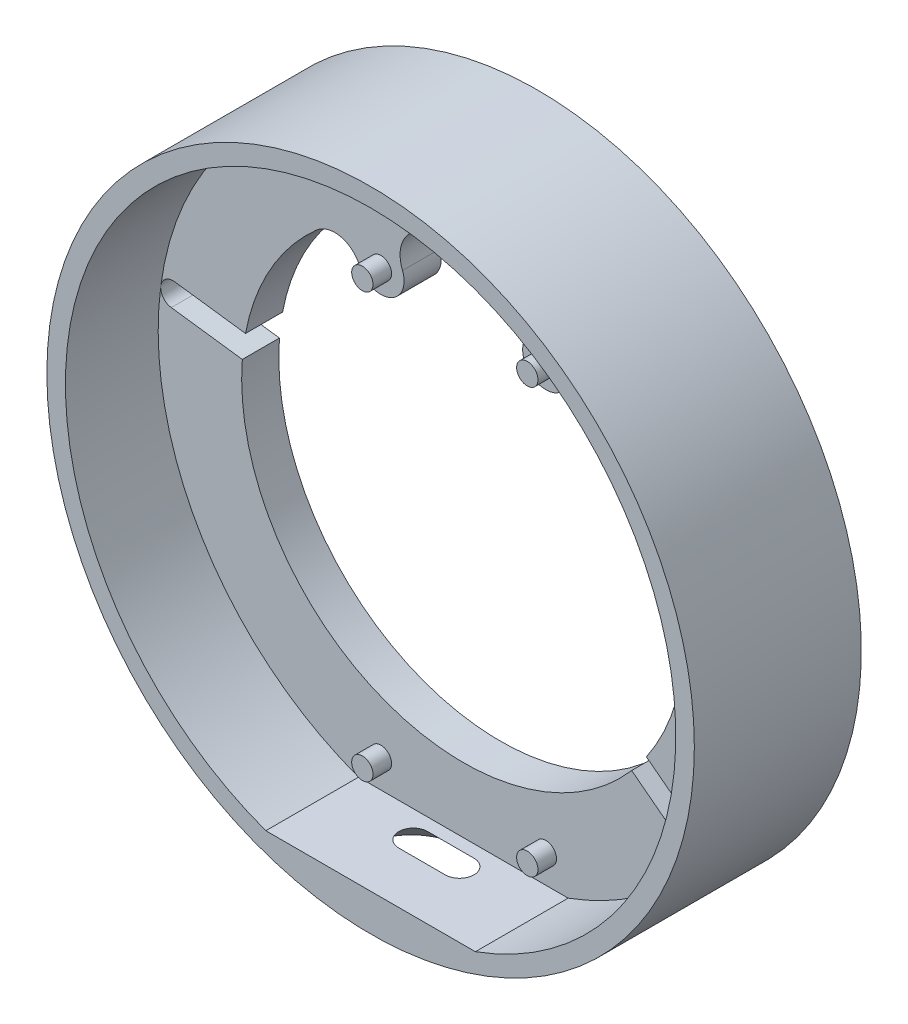
SolidWorks part; units mm, degrees
ref_plane "Plan de face" through (0, 0, 0) normal (0, 0, 1) x (1, 0, 0)
ref_plane "Plan de dessus" through (0, 0, 0) normal (0, 1, 0) x (1, 0, 0)
ref_plane "Plan de droite" through (0, 0, 0) normal (1, 0, 0) x (0, 0, -1)
sketch "Esquisse_carte_affichage" plane through (0, 0, 0) normal (0, 0, 1) x (1, 0, 0)
  circle A0 centre (19.25, 25.1) radius 0.5
  circle A1 centre (25.07, -19.23) radius 0.5
  circle A2 centre (29.18, 12.09) radius 0.5
  circle A3 centre (31.32, -4.14) radius 0.5
  circle A4 centre (-29.21, -12.07) radius 0.5
  circle A5 centre (-31.32, 4.14) radius 0.5
  circle A6 centre (-26.4935, -7.4094) radius 0.25
  circle A7 centre (-23.6728, -14.0139) radius 0.25
  circle A8 centre (-19.2392, -19.6637) radius 0.25
  circle A9 centre (-13.4943, -23.973) radius 0.25
  circle A10 centre (-6.8298, -26.6487) radius 0.25
  circle A11 centre (0.3, -27.5085) radius 0.25
  circle A12 centre (7.4094, -26.4935) radius 0.25
  circle A13 centre (14.0139, -23.6728) radius 0.25
  circle A14 centre (19.6637, -19.2392) radius 0.25
  circle A15 centre (23.973, -13.4943) radius 0.25
  circle A16 centre (26.6487, -6.8298) radius 0.25
  circle A17 centre (27.5085, 0.3) radius 0.25
  circle A18 centre (26.4935, 7.4094) radius 0.25
  circle A19 centre (23.6728, 14.0139) radius 0.25
  circle A20 centre (19.2392, 19.6637) radius 0.25
  circle A21 centre (13.4943, 23.973) radius 0.25
  circle A22 centre (6.8298, 26.6487) radius 0.25
  circle A23 centre (-0.3, 27.5085) radius 0.25
  circle A24 centre (-7.4094, 26.4935) radius 0.25
  circle A25 centre (-14.0139, 23.6728) radius 0.25
  circle A26 centre (-19.6637, 19.2392) radius 0.25
  circle A27 centre (-23.973, 13.4943) radius 0.25
  circle A28 centre (-26.6487, 6.8298) radius 0.25
  circle A29 centre (-27.5085, -0.3) radius 0.25
  circle A30 centre (-30.2, -7.1) radius 0.25
  circle A31 centre (-26.5986, -15.746) radius 0.25
  circle A32 centre (-28.1305, -7.8674) radius 0.25
  circle A33 centre (-21.6169, -22.0937) radius 0.25
  circle A34 centre (-25.1358, -14.8801) radius 0.25
  circle A35 centre (-15.162, -26.9359) radius 0.25
  circle A36 centre (-20.428, -20.8785) radius 0.25
  circle A37 centre (-7.6738, -29.9423) radius 0.25
  circle A38 centre (-14.3281, -25.4544) radius 0.25
  circle A39 centre (0.3371, -30.9082) radius 0.25
  circle A40 centre (-7.252, -28.2956) radius 0.25
  circle A41 centre (8.3254, -29.7678) radius 0.25
  circle A42 centre (0.3185, -29.2082) radius 0.25
  circle A43 centre (15.746, -26.5986) radius 0.25
  circle A44 centre (7.8674, -28.1305) radius 0.25
  circle A45 centre (22.0937, -21.6169) radius 0.25
  circle A46 centre (14.8801, -25.1358) radius 0.25
  circle A47 centre (26.9359, -15.162) radius 0.25
  circle A48 centre (20.8785, -20.428) radius 0.25
  circle A49 centre (29.9423, -7.6738) radius 0.25
  circle A50 centre (25.4544, -14.3281) radius 0.25
  circle A51 centre (30.9082, 0.3371) radius 0.25
  circle A52 centre (28.2956, -7.252) radius 0.25
  circle A53 centre (29.7678, 8.3254) radius 0.25
  circle A54 centre (29.2082, 0.3185) radius 0.25
  circle A55 centre (26.5986, 15.746) radius 0.25
  circle A56 centre (28.1305, 7.8674) radius 0.25
  circle A57 centre (21.6169, 22.0937) radius 0.25
  circle A58 centre (25.1358, 14.8801) radius 0.25
  circle A59 centre (15.162, 26.9359) radius 0.25
  circle A60 centre (20.428, 20.8785) radius 0.25
  circle A61 centre (7.6738, 29.9423) radius 0.25
  circle A62 centre (14.3281, 25.4544) radius 0.25
  circle A63 centre (-0.3371, 30.9082) radius 0.25
  circle A64 centre (7.252, 28.2956) radius 0.25
  circle A65 centre (-8.3254, 29.7678) radius 0.25
  circle A66 centre (-0.3185, 29.2082) radius 0.25
  circle A67 centre (-15.746, 26.5986) radius 0.25
  circle A68 centre (-7.8674, 28.1305) radius 0.25
  circle A69 centre (-22.0937, 21.6169) radius 0.25
  circle A70 centre (-14.8801, 25.1358) radius 0.25
  circle A71 centre (-26.9359, 15.162) radius 0.25
  circle A72 centre (-20.8785, 20.428) radius 0.25
  circle A73 centre (-29.9423, 7.6738) radius 0.25
  circle A74 centre (-25.4544, 14.3281) radius 0.25
  circle A75 centre (-30.9082, -0.3371) radius 0.25
  circle A76 centre (-28.2956, 7.252) radius 0.25
  circle A77 centre (0, 0) radius 26.162
  circle A78 centre (0, 0) radius 32.766
  dimension "D1" = 65.532
  dimension "D2" = 52.324
sketch "Esquisse_carte_mère" plane through (0, 0, 0) normal (0, 0, 1) x (1, 0, 0)
  line L0 (-11.3435, -28.5174) -> (-11.0897, -29.13)
  line L1 (-11.0897, -29.13) -> (-10.6861, -29.6561)
  line L2 (-10.6861, -29.6561) -> (-10.16, -30.0597)
  line L3 (-10.16, -30.0597) -> (-9.5474, -30.3135)
  line L4 (-9.5474, -30.3135) -> (-8.89, -30.4)
  line L5 (-8.89, -30.4) -> (-2.413, -30.4)
  line L6 (-2.413, -30.4) -> (-1.905, -29.892)
  line L7 (-1.905, -29.892) -> (1.905, -29.892)
  line L8 (1.905, -29.892) -> (2.413, -30.4)
  line L9 (2.413, -30.4) -> (8.89, -30.4)
  line L10 (8.89, -30.4) -> (9.5474, -30.3135)
  line L11 (9.5474, -30.3135) -> (10.16, -30.0597)
  line L12 (10.16, -30.0597) -> (10.6861, -29.6561)
  line L13 (10.6861, -29.6561) -> (11.0897, -29.13)
  line L14 (11.0897, -29.13) -> (11.3435, -28.5174)
  line L15 (11.3435, -28.5174) -> (11.43, -27.86)
  line L16 (11.43, -27.86) -> (11.43, 17.86)
  line L17 (11.43, 17.86) -> (11.3435, 18.5174)
  line L18 (11.3435, 18.5174) -> (11.0897, 19.13)
  line L19 (11.0897, 19.13) -> (10.6861, 19.6561)
  line L20 (10.6861, 19.6561) -> (10.16, 20.0597)
  line L21 (10.16, 20.0597) -> (9.5474, 20.3135)
  line L22 (9.5474, 20.3135) -> (8.89, 20.4)
  line L23 (8.89, 20.4) -> (-8.89, 20.4)
  line L24 (-8.89, 20.4) -> (-9.5474, 20.3135)
  line L25 (-9.5474, 20.3135) -> (-10.16, 20.0597)
  line L26 (-10.16, 20.0597) -> (-10.6861, 19.6561)
  line L27 (-10.6861, 19.6561) -> (-11.0897, 19.13)
  line L28 (-11.0897, 19.13) -> (-11.3435, 18.5174)
  line L29 (-11.3435, 18.5174) -> (-11.43, 17.86)
  line L30 (-11.43, 17.86) -> (-11.43, -27.86)
  line L31 (-11.43, -27.86) -> (-11.3435, -28.5174)
  line L32 (8.9522, -28.0199) -> (-18113.3609, 46572.2136) construction
  line L33 (-8.9266, -27.9541) -> (18113.3865, 46572.2795) construction
  circle A0 centre (-3.3, -25.05) radius 0.4
  circle A1 centre (3.3, -25.05) radius 0.4
  circle A2 centre (-3.6, -27.86) radius 0.45
  circle A3 centre (3.6, -27.86) radius 0.45
  circle A4 centre (10.16, 14.05) radius 0.5
  circle A5 centre (10.16, 11.51) radius 0.5
  circle A6 centre (10.16, 8.97) radius 0.5
  circle A7 centre (10.16, 6.43) radius 0.5
  circle A8 centre (10.16, 3.89) radius 0.5
  circle A9 centre (10.16, 1.35) radius 0.5
  circle A10 centre (10.16, -1.19) radius 0.5
  circle A11 centre (10.16, -3.73) radius 0.5
  circle A12 centre (10.16, -6.27) radius 0.5
  circle A13 centre (10.16, -8.81) radius 0.5
  circle A14 centre (10.16, -11.35) radius 0.5
  circle A15 centre (10.16, -13.89) radius 0.5
  circle A16 centre (-10.16, -24.05) radius 0.5
  circle A17 centre (-10.16, -21.51) radius 0.5
  circle A18 centre (-10.16, -18.97) radius 0.5
  circle A19 centre (-10.16, -16.43) radius 0.5
  circle A20 centre (-10.16, -13.89) radius 0.5
  circle A21 centre (-10.16, -11.35) radius 0.5
  circle A22 centre (-10.16, -8.81) radius 0.5
  circle A23 centre (-10.16, -6.27) radius 0.5
  circle A24 centre (-10.16, -3.73) radius 0.5
  circle A25 centre (-10.16, -1.19) radius 0.5
  circle A26 centre (-10.16, 1.35) radius 0.5
  circle A27 centre (-10.16, 3.89) radius 0.5
  circle A28 centre (-10.16, 6.43) radius 0.5
  circle A29 centre (-10.16, 8.97) radius 0.5
  circle A30 centre (-10.16, 11.51) radius 0.5
  circle A31 centre (-10.16, 14.05) radius 0.5
  circle A32 centre (-8.89, -27.86) radius 1.25
  circle A33 centre (8.89, -27.86) radius 1.25
  circle A34 centre (-8.89, 17.86) radius 1.25
  circle A35 centre (8.89, 17.86) radius 1.25
  circle A36 centre (-1.95, -25.955) radius 0.35
  circle A37 centre (1.95, -25.955) radius 0.35
  circle A38 centre (-2.2, 15.706) radius 0.45
  circle A39 centre (3.048, -15.795) radius 0.25
  circle A40 centre (1.016, -20.875) radius 0.25
  circle A41 centre (-6.223, -9.826) radius 0.25
  circle A42 centre (-6.096, -16.43) radius 0.25
  circle A43 centre (7.3914, -2.0028) radius 0.25
  circle A44 centre (7.366, -18.462) radius 0.25
  circle A45 centre (-1.905, 12.018) radius 0.25
  circle A46 centre (1.905, 9.224) radius 0.25
  circle A47 centre (-5.715, -21.129) radius 0.25
  circle A48 centre (-4.064, -1.571) radius 0.25
  circle A49 centre (-8.509, -22.78) radius 0.25
  circle A50 centre (0.2286, -14.5758) radius 0.25
  circle A51 centre (0.508, 7.446) radius 0.25
  circle A52 centre (0.635, 8.589) radius 0.25
  circle A53 centre (-7.112, 0.334) radius 0.25
  circle A54 centre (4.953, -15.795) radius 0.25
  circle A55 centre (0, 10.494) radius 0.25
  circle A56 centre (-4.191, -16.43) radius 0.25
  circle A57 centre (-0.889, -17.573) radius 0.25
  circle A58 centre (5.842, -10.715) radius 0.25
  circle A59 centre (2.159, -17.446) radius 0.25
  circle A60 centre (0, -27.987) radius 0.25
  circle A61 centre (-1.397, 4.271) radius 0.25
  circle A62 centre (-5.207, 1.985) radius 0.25
  circle A63 centre (-0.381, -6.651) radius 0.25
  circle A64 centre (6.858, 8.462) radius 0.25
  circle A65 centre (5.207, 3.128) radius 0.25
  circle A66 centre (2.667, 4.525) radius 0.25
  circle A67 centre (5.08, 11.764) radius 0.25
  circle A68 centre (0, 14.431) radius 0.25
  circle A69 centre (-1.778, 8.716) radius 0.25
  circle A70 centre (-2.921, 4.271) radius 0.25
  circle A71 centre (-5.588, 3.128) radius 0.25
  circle A72 centre (-1.905, -19.732) radius 0.25
  circle A73 centre (-5.842, -8.683) radius 0.25
  circle A74 centre (-3.048, -20.113) radius 0.25
  circle A75 centre (-6.604, -7.667) radius 0.25
  circle A76 centre (-5.207, -10.842) radius 0.25
  circle A77 centre (10.668, -26.082) radius 0.25
  circle A78 centre (5.969, -4.365) radius 0.25
  circle A79 centre (5.08, -9.191) radius 0.25
  circle A80 centre (-3.81, -3.349) radius 0.25
  circle A81 centre (-4.953, -9.699) radius 0.25
  circle A82 centre (3.048, 6.43) radius 0.25
  circle A83 centre (5.969, -3.222) radius 0.25
  circle A84 centre (6.858, -7.667) radius 0.25
  circle A85 centre (6.477, 6.303) radius 0.25
  circle A86 centre (-1.27, 10.367) radius 0.25
  circle A87 centre (-1.0922, -0.1994) radius 0.25
  circle A88 centre (0.508, -0.428) radius 0.25
  circle A89 centre (4.318, -17.065) radius 0.25
  circle A90 centre (1.524, 4.144) radius 0.25
  circle A91 centre (-2.921, -1.444) radius 0.25
  circle A92 centre (3.302, -10.08) radius 0.25
  circle A93 centre (-3.81, -10.08) radius 0.25
  circle A94 centre (-5.08, -6.778) radius 0.25
  point P222 (0, -5)
  dimension "D5" = 2.5
  dimension "D1" = 2.54
  dimension "D2" = 2.54
  dimension "D3" = 2.54
  dimension "D4" = 2.54
sketch "Esquisse_support" plane through (0, 0, 0) normal (0, 0, 1) x (1, 0, 0)
  line L0 (0, 0) -> (0, -50000) construction
  line L1 (0, 0) -> (-31.32, 4.14) construction
  line L2 (0, 0) -> (19.25, 25.1) construction
  line L3 (0, 0) -> (25.07, -19.23) construction
  line L4 (25.07, -19.23) -> (30456.2807, 39653.7005) construction
  line L5 (19.25, 25.1) -> (39694.4792, -30403.1136) construction
  line L6 (-31.32, 4.14) -> (6520.8813, 49572.9675) construction
  line L7 (-31.1487, 5.4363) -> (-23.4871, 4.4235)
  line L8 (-31.4913, 2.8437) -> (-23.8298, 1.831)
  line L9 (18.2437, 25.8718) -> (13.5179, 19.7098)
  line L10 (20.2563, 24.3282) -> (15.5305, 18.1663)
  line L11 (25.8637, -18.1952) -> (19.7291, -13.4897)
  line L12 (24.2763, -20.2648) -> (18.1417, -15.5592)
  line L13 (-8.89, 17.86) -> (46591.3436, 18140.1731) construction
  line L14 (8.89, 17.86) -> (-46591.3436, 18140.1731) construction
  line L15 (11.22, 16.9539) -> (13.5179, 19.7098)
  line L16 (72498.2044, -186428.9542) -> (-90602.6131, 232973.148) construction
  line L17 (-72498.1788, -186428.8884) -> (90602.6387, 232973.2138) construction
  circle A0 centre (0, 0) radius 32.9 construction
  circle A1 centre (0, 0) radius 34.9
  arc A2 (-32.6163, 4.3113) -> (-31.4913, 2.8437) centre (-31.32, 4.14) ccw
  arc A3 (-32.6163, 4.3113) -> (-31.1487, 5.4363) centre (-31.32, 4.14) cw
  arc A4 (20.0218, 26.1063) -> (18.2437, 25.8718) centre (19.25, 25.1) ccw
  arc A5 (20.0218, 26.1063) -> (20.2563, 24.3282) centre (19.25, 25.1) cw
  arc A6 (26.1048, -20.0237) -> (25.8637, -18.1952) centre (25.07, -19.23) ccw
  arc A7 (26.1048, -20.0237) -> (24.2763, -20.2648) centre (25.07, -19.23) cw
  arc A8 (-23.4871, 4.4235) -> (13.5179, 19.7098) centre (0, 0) cw construction
  arc A9 (-23.8298, 1.831) -> (18.1417, -15.5592) centre (0, 0) ccw
  arc A10 (19.7291, -13.4897) -> (15.5305, 18.1663) centre (0, 0) ccw
  arc A11 (-6.56, 18.7661) -> (-11.22, 16.9539) centre (-8.89, 17.86) cw
  arc A12 (6.56, 18.7661) -> (11.22, 16.9539) centre (8.89, 17.86) ccw
  arc A13 (-6.56, 18.7661) -> (-4.1838, 23.531) centre (-3.28, 20.1053) cw
  arc A14 (6.56, 18.7661) -> (4.1838, 23.531) centre (3.28, 20.1053) ccw
  arc A15 (-11.22, 16.9539) -> (-15.8818, 17.86) centre (-13.8724, 15.7529) ccw
  arc A16 (-23.4871, 4.4235) -> (-15.8818, 17.86) centre (0, 0) cw
  arc A17 (-4.1838, 23.531) -> (4.1838, 23.531) centre (0, 0) cw
  point P37 (-4.1838, 23.531)
  dimension "D1" = 65.8
  dimension "D2" = 69.8
  dimension "D12" = 2.5
  dimension "D13" = 2.5
  dimension "D3" = 90
  dimension "D4" = 90
  dimension "D5" = 90
  dimension "D7" = 90
  dimension "D8" = 90
  dimension "D9" = 90
  dimension "D10" = 90
  dimension "D11" = 90
extrude "Boss.-Extru.1" add sketch "Esquisse_support" along normal blind 4 contours A1 A13 A17 A14 A12 L15 L9 A4 A5 L10 A10 L11 A6 A7 L12 A9 L8 A2 A3 L7 A16 A15 A11
sketch "Esquisse6" plane through (0, 0, 4) normal (0, 0, 1) x (1, 0, 0)
  line L0 (0, 0) -> (0, -50000) construction
  circle A0 centre (-8.89, 17.86) radius 1.15
  circle A1 centre (-8.89, -27.86) radius 1.15
  circle A2 centre (8.89, -27.86) radius 1.15
  circle A3 centre (8.89, 17.86) radius 1.15
  dimension "D1" = 2.3
  dimension "D2" = 2.3
extrude "Boss.-Extru.2" add sketch "Esquisse6" along normal blind 2
sketch "Esquisse7" plane through (0, 0, 0) normal (0, 0, -1) x (-1, 0, 0)
  circle A0 centre (0, 0) radius 34.9
  circle A1 centre (0, 0) radius 32.9
extrude "Boss.-Extru.3" add sketch "Esquisse7" along normal blind 4
sketch "Esquisse8" plane through (0, 0, 4) normal (0, 0, 1) x (1, 0, 0)
  line L0 (0, 0) -> (0, -50000) construction
  line L1 (-11.296, -30.9) -> (11.296, -30.9)
  line L2 (-8.89, -30.4) -> (-2.413, -30.4) construction
  circle A0 centre (0, 0) radius 34.9
  circle A1 centre (0, 0) radius 32.9 construction
  arc A2 (-11.296, -30.9) -> (11.296, -30.9) centre (0, 0) cw
  point P9 (0, -30.9)
  circle M5 centre (0, 0) radius 34.9
  dimension "D2" = 0.5
extrude "Boss.-Extru.5" add sketch "Esquisse8" along normal blind 10 contours A2 L1 M5
sketch "Ouverture_USB" plane through (0, -30.9, 0) normal (0, 1, 0) x (1, 0, 0)
  line L1 (-2.504, -6.9) -> (2.496, -6.9) construction
  line L2 (-2.504, -5.35) -> (2.496, -5.35)
  line L3 (-2.504, -8.45) -> (2.496, -8.45)
  line L9 (11.296, -14) -> (11.296, -4) construction
  line L10 (-11.296, -4) -> (11.296, -4) construction
  arc A0 (-2.504, -5.35) -> (-2.504, -8.45) centre (-2.504, -6.9) ccw
  arc A1 (2.496, -8.45) -> (2.496, -5.35) centre (2.496, -6.9) ccw
  point P2 (-0.004, -6.9)
  point P6 (-0.004, -5.35)
  point P9 (0, -4)
  point P10 (0, 0)
  point P19 (4.046, -6.9)
  point P21 (-4.054, -6.9)
  dimension "D1" = 7.25
  dimension "D2" = 3.1
  dimension "D3" = 1.35
  dimension "D4" = 8.1
extrude "Enlèv. mat.-Extru.3" cut sketch "Ouverture_USB" against normal through all draft 49 contours L2 A1 L3 A0 draft outward yes
